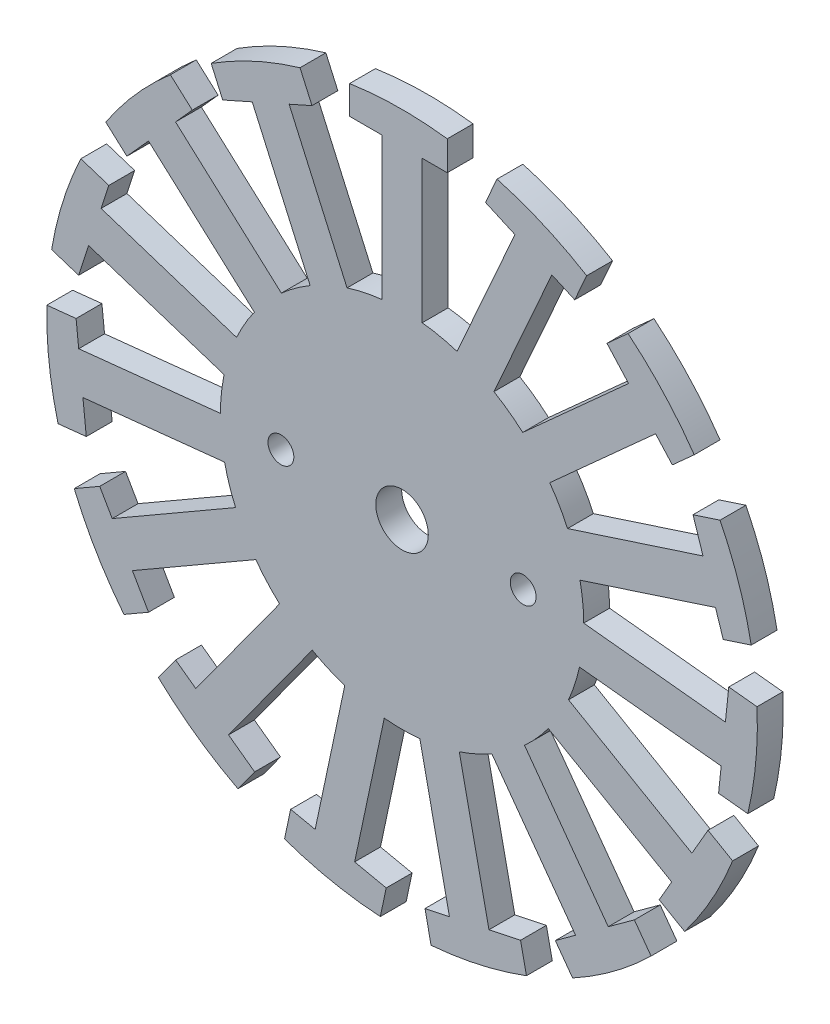
SolidWorks part; units mm, degrees
ref_plane "正面" through (0, 0, 0) normal (0, 0, 1) x (1, 0, 0)
ref_plane "平面" through (0, 0, 0) normal (0, 1, 0) x (1, 0, 0)
ref_plane "右側面" through (0, 0, 0) normal (1, 0, 0) x (0, 0, -1)
sketch "ｽｹｯﾁ1" plane through (0, 0, 0) normal (0, 0, 1) x (1, 0, 0)
  line L0 (0, 0) -> (0, 40)
  line L1 (0, 0) -> (-2.5, 0)
  line L2 (-2.5, 0) -> (-2.5, 40)
  line L3 (0, 0) -> (2.5, 0)
  line L4 (2.5, 0) -> (2.5, 40)
  line L6 (-2.5, 40) -> (-6.5, 40)
  line L7 (2.5, 40) -> (5.6, 40)
  line L8 (5.6, 40) -> (5.6, 43.6422)
  line L9 (-6.5, 40) -> (-6.5, 43.5172)
  arc A1 (5.6, 43.6422) -> (-6.5, 43.5172) centre (0, 0) ccw
  circle A2 centre (0, 0) radius 22.5
  dimension "D2" = 88
  dimension "D3" = 45
  dimension "D4" = 2.5
  dimension "D5" = 2.5
  dimension "D7" = 6.5
  dimension "D8" = 5.6
extrude "ﾎﾞｽ - 押し出し2" add sketch "ｽｹｯﾁ1" along normal blind 3.2 contours L2 A2 L4 L3 L1
pattern_circular "円形ﾊﾟﾀｰﾝ2" count 15 over 360 about axis through (0, 0, 0) along (0, 0, 1) of "ﾎﾞｽ - 押し出し2"
sketch "ｽｹｯﾁ3" plane through (0, 0, 3.2) normal (0, 0, 1) x (1, 0, 0)
  circle A0 centre (0, 0) radius 3.25
  dimension "D1" = 6.5
extrude "ｶｯﾄ - 押し出し2" cut sketch "ｽｹｯﾁ3" against normal blind 3.2
sketch "ｽｹｯﾁ5" plane through (0, 0, 3.2) normal (0, 0, 1) x (1, 0, 0)
  line L0 (-15, 0) -> (15, 0)
  circle A0 centre (-15, 0) radius 1.6
  circle A1 centre (15, 0) radius 1.6
  point P3 (0, 0)
  point P4 (0, 0)
  point P5 (0, 0)
  dimension "D1" = 3.2
extrude "ｶｯﾄ - 押し出し3" cut sketch "ｽｹｯﾁ5" against normal blind 10 contours A0 | A1
